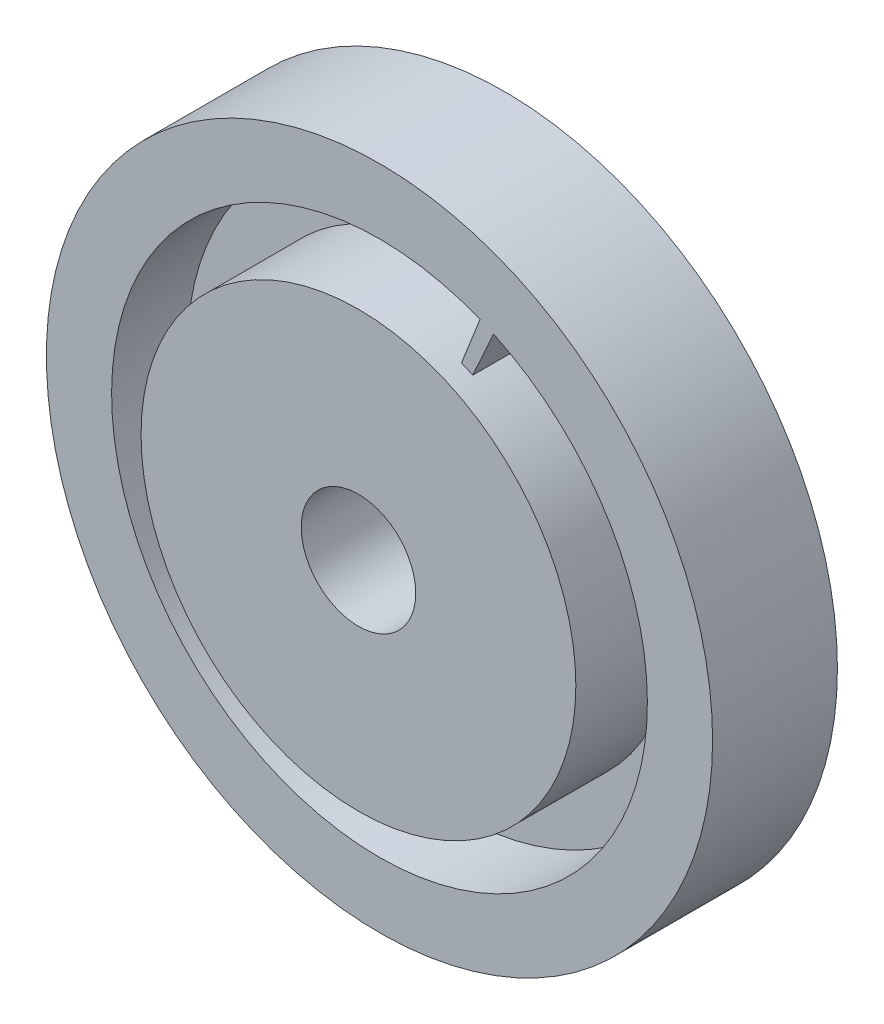
SolidWorks part; units mm, degrees
ref_plane "Front Plane" through (0, 0, 0) normal (0, 0, 1) x (1, 0, 0)
ref_plane "Top Plane" through (0, 0, 0) normal (0, 1, 0) x (1, 0, 0)
ref_plane "Right Plane" through (0, 0, 0) normal (1, 0, 0) x (0, 0, -1)
sketch "Sketch1" plane through (0, 0, 0) normal (0, 0, 1) x (1, 0, 0)
  circle A0 centre (0, 0) radius 23.75
extrude "Boss-Extrude1" add sketch "Sketch1" along normal blind 8.9
sketch "Sketch3" plane through (0, 0, 0) normal (0, 0, -1) x (-1, 0, 0)
  circle A0 centre (0, 0) radius 15.5
extrude "Boss-Extrude2" add sketch "Sketch3" against normal blind 10.4
sketch "Sketch4" plane through (0, 0, 8.9) normal (0, 0, -1) x (-1, 0, 0)
  line L0 (-5.8487, 14.3542) -> (-7.1676, 17.7041)
  line L1 (-6.6484, 14.0018) -> (-8.1285, 17.284)
  arc A0 (-8.1285, 17.284) -> (-7.1676, 17.7041) centre (0, 0) ccw
  arc A1 (-5.8487, 14.3542) -> (-6.6484, 14.0018) centre (0, 0) cw
extrude "Cut-Extrude1" cut sketch "Sketch4" along normal blind 5.4
sketch "Sketch5" plane through (0, 0, 10.4) normal (0, 0, 1) x (1, 0, 0)
  circle A0 centre (0, 0) radius 4.08
extrude "Cut-Extrude2" cut sketch "Sketch5" against normal up to next
